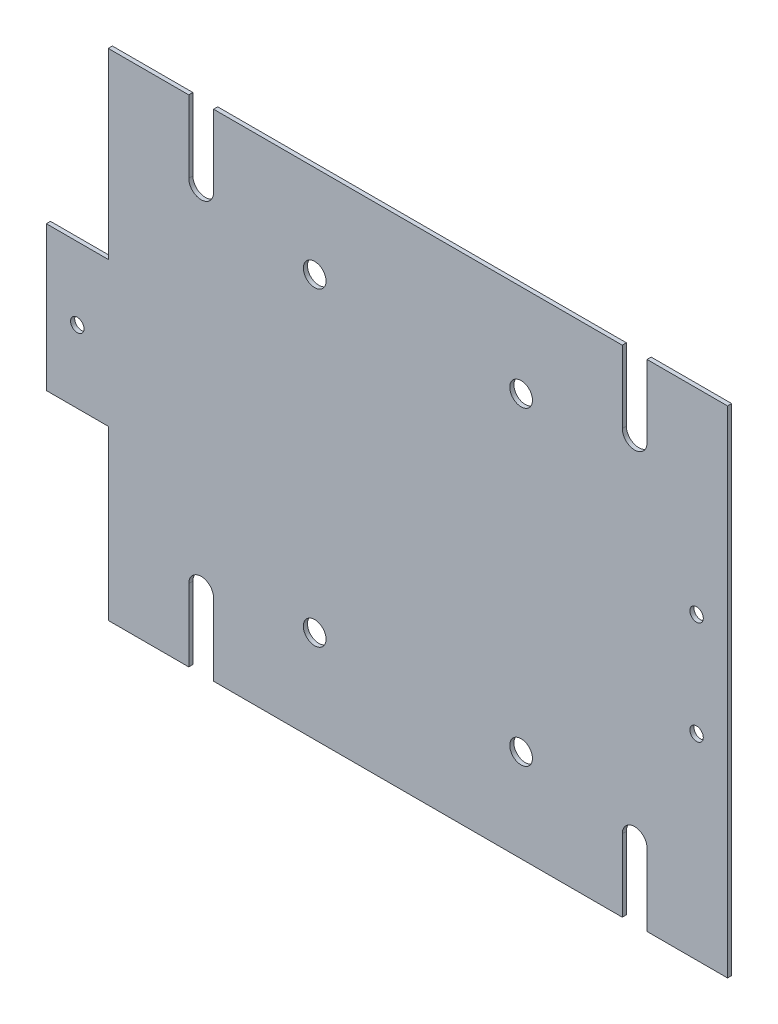
SolidWorks part; units mm, degrees
material "Galvanized Steel"
ref_plane "Front Plane" through (0, 0, 0) normal (0, 0, 1) x (1, 0, 0)
ref_plane "Top Plane" through (0, 0, 0) normal (0, 1, 0) x (1, 0, 0)
ref_plane "Right Plane" through (0, 0, 0) normal (1, 0, 0) x (0, 0, -1)
sketch "Sketch1" plane through (0, 0, 0) normal (0, 0, 1) x (1, 0, 0)
  line L1 (68.9488, 58.3662) -> (29.9488, 58.3662)
  line L2 (68.9488, 58.3662) -> (68.9488, -26.6338)
  line L3 (68.9488, -181.6338) -> (29.9488, -181.6338)
  line L4 (-231.0512, 58.3662) -> (-231.0512, -30.1799)
  line L7 (-231.0512, -30.1799) -> (-261.0512, -30.1799)
  line L8 (-261.0512, -30.1799) -> (-261.0512, -100.1799)
  line L9 (-261.0512, -100.1799) -> (-231.0512, -100.1799)
  line L10 (-231.0512, -100.1799) -> (-231.0512, -181.6338)
  line L11 (68.9488, -26.6338) -> (68.9488, -181.6338)
  line L12 (17.9488, -181.6338) -> (-180.0512, -181.6338)
  line L13 (-180.0512, 58.3662) -> (-180.0512, 23.3662)
  line L14 (-192.0512, 58.3662) -> (-192.0512, 23.3662)
  line L16 (-192.0512, -181.6338) -> (-192.0512, -146.6338)
  line L17 (-180.0512, -181.6338) -> (-180.0512, -146.6338)
  line L18 (-192.0512, -181.6338) -> (-231.0512, -181.6338)
  line L19 (29.9488, -146.6338) -> (29.9488, -181.6338)
  line L20 (17.9488, -146.6338) -> (17.9488, -181.6338)
  line L21 (-192.0512, 58.3662) -> (-231.0512, 58.3662)
  line L22 (29.9488, 58.3662) -> (29.9488, 23.3662)
  line L23 (17.9488, 58.3662) -> (17.9488, 23.3662)
  line L24 (17.9488, 58.3662) -> (-180.0512, 58.3662)
  circle A0 centre (-131.0512, 13.4862) radius 5.5
  arc A1 (-192.0512, 23.3662) -> (-180.0512, 23.3662) centre (-186.0512, 23.3662) ccw
  circle A2 centre (53.9488, -36.6338) radius 3.25
  arc A3 (-180.0512, -146.6338) -> (-192.0512, -146.6338) centre (-186.0512, -146.6338) ccw
  arc A4 (29.9488, -146.6338) -> (17.9488, -146.6338) centre (23.9488, -146.6338) ccw
  circle A5 centre (53.9488, -86.6338) radius 3.25
  circle A6 centre (-246.0512, -65.1799) radius 3.25
  arc A7 (17.9488, 23.3662) -> (29.9488, 23.3662) centre (23.9488, 23.3662) ccw
  circle A8 centre (-31.0512, -136.7538) radius 5.5
  circle A9 centre (-131.0512, -136.7538) radius 5.5
  circle A10 centre (-31.0512, 13.4862) radius 5.5
  point P14 (-186.0512, 50.7838)
  point P21 (-186.0512, -182.4408)
  point P26 (23.9488, -182.4408)
  point P33 (23.9488, 50.7838)
  dimension "D18" = 95
  dimension "D19" = 6.5
  dimension "D20" = 6.5
  dimension "D21" = 6.5
  dimension "D27" = 6.5
  dimension "D32" = 11
  dimension "D34" = 11
  dimension "D35" = 11
  dimension "D23" = 11
  dimension "D6" = 15
  dimension "D7" = 50
  dimension "D1" = 240
  dimension "D2" = 300
  dimension "D3" = 30
  dimension "D4" = 70
  dimension "D5" = 45
  dimension "D8" = 12
  dimension "D9" = 12
  dimension "D10" = 39
  dimension "D11" = 39
  dimension "D12" = 12
  dimension "D13" = 12
  dimension "D14" = 35
  dimension "D15" = 35
  dimension "D16" = 35
  dimension "D17" = 35
  dimension "D28" = 15
  dimension "D29" = 35
extrude "Boss-Extrude1" add sketch "Sketch1" along normal blind 2
